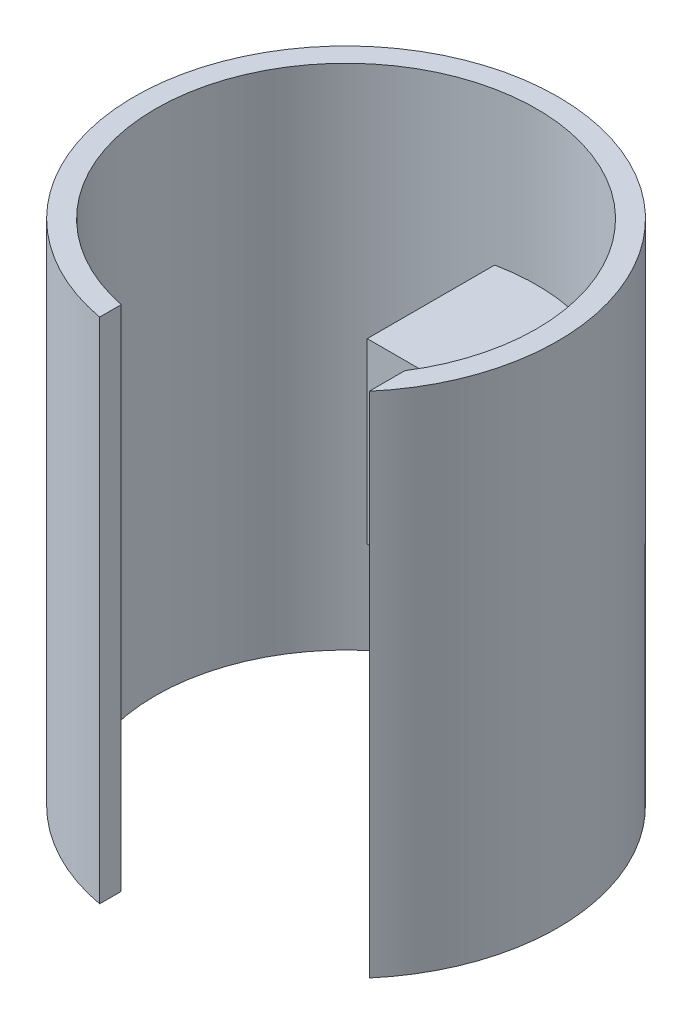
SolidWorks part; units mm, degrees
ref_plane "Alzado" through (0, 0, 0) normal (0, 0, 1) x (1, 0, 0)
ref_plane "Planta" through (0, 0, 0) normal (0, 1, 0) x (1, 0, 0)
ref_plane "Vista lateral" through (0, 0, 0) normal (1, 0, 0) x (0, 0, -1)
sketch "Croquis1" plane through (0, 0, 0) normal (0, 1, 0) x (1, 0, 0)
  circle A0 centre (0, 0) radius 50
  dimension "D1" = 100
extrude "Saliente-Extruir1" add sketch "Croquis1" along normal blind 120
sketch "Croquis2" plane through (0, 120, 0) normal (0, 1, 0) x (1, 0, 0)
  circle A0 centre (0, 0) radius 45
  dimension "D1" = 90
extrude "Cortar-Extruir1" cut sketch "Croquis2" against normal up to next
sketch "Croquis4" plane through (0, 0, 0) normal (0, 0, 1) x (1, 0, 0)
  line L1 (-9, 42) -> (38, 42)
  line L2 (-9, 42) -> (-9, 84)
  line L3 (-9, 84) -> (38, 84)
  line L4 (38, 42) -> (38, 84)
  line L5 (-9, 42) -> (38, 84) construction
  line L6 (-9, 84) -> (38, 42) construction
  line L7 (-50, 0) -> (50, 0) construction
  point P0 (14.5, 63)
  dimension "D1" = 42
  dimension "D2" = 47
  dimension "D3" = 42
  dimension "D4" = 14.5
extrude "Saliente-Extruir2" add sketch "Croquis4" against normal up to surface (44.0908 mm away)
sketch "Croquis5" plane through (0, 0, 0) normal (0, 0, 1) x (1, 0, 0)
  line L0 (-9, 42) -> (38, 42) construction
  line L1 (-9, 42) -> (38, 42)
  line L2 (-9, 42) -> (-9, 84)
  line L3 (-9, 84) -> (38, 84)
  line L4 (38, 42) -> (38, 84)
  line L5 (-9, 42) -> (38, 84) construction
  line L6 (-9, 84) -> (38, 42) construction
  line L7 (-9, 84) -> (-9, 42) construction
  point P0 (14.5, 63)
extrude "Cortar-Extruir2" cut sketch "Croquis5" against normal blind 14
sketch "Croquis7" plane through (0, 120, 0) normal (0, 1, 0) x (1, 0, 0)
  line L0 (-9, -44.0908) -> (-9, -49.1833)
  line L1 (38, -24.1039) -> (38, -32.4962)
  line L2 (38, 24.1039) -> (38, 14) construction
  line L3 (-9, 44.0908) -> (-9, 14) construction
  circle A0 centre (0, 0) radius 45 construction
  circle A1 centre (0, 0) radius 50 construction
  arc A2 (-9, -44.0908) -> (38, -24.1039) centre (0, 0) ccw
  arc A3 (-9, -49.1833) -> (38, -32.4962) centre (0, 0) ccw
extrude "Cortar-Extruir3" cut sketch "Croquis7" against normal up to next
